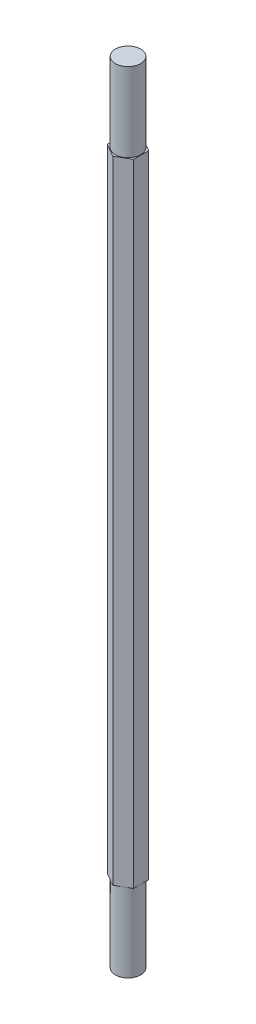
SolidWorks part; units mm, degrees
ref_plane "Front Plane" through (0, 0, 0) normal (0, 0, 1) x (1, 0, 0)
ref_plane "Top Plane" through (0, 0, 0) normal (0, 1, 0) x (1, 0, 0)
ref_plane "Right Plane" through (0, 0, 0) normal (1, 0, 0) x (0, 0, -1)
sketch "Sketch1" plane through (0, 0, 0) normal (0, 1, 0) x (1, 0, 0)
  line L2 (3.3102, -4.4201) -> (3.3102, -0.7625)
  line L3 (3.3102, -0.7625) -> (0.1408, 1.0631)
  line L4 (0.1408, 1.0631) -> (-3.0287, -0.7625)
  line L5 (-3.0287, -0.7625) -> (-3.0287, -4.4201)
  line L6 (-3.0287, -4.4201) -> (0.1408, -6.2457)
  line L7 (0.1408, -6.2457) -> (3.3102, -4.4201)
  point P8 (3.3102, -2.5913)
extrude "Boss-Extrude1" add sketch "Sketch1" along normal blind 190.5
sketch "Sketch2" plane through (0, 190.5, 0) normal (0, 1, 0) x (1, 0, 0)
  circle A0 centre (0.1463, -2.5913) radius 3.048
extrude "Cut-Extrude1" cut sketch "Sketch2" against normal blind 19.05 flip side to cut
ref_plane "Plane1" through (0, 95.25, 0) normal (0, 1, 0) x (1, 0, 0)
mirror "Mirror1" about plane through (0, 95.25, 0) normal (0, 1, 0) of "Cut-Extrude1"
